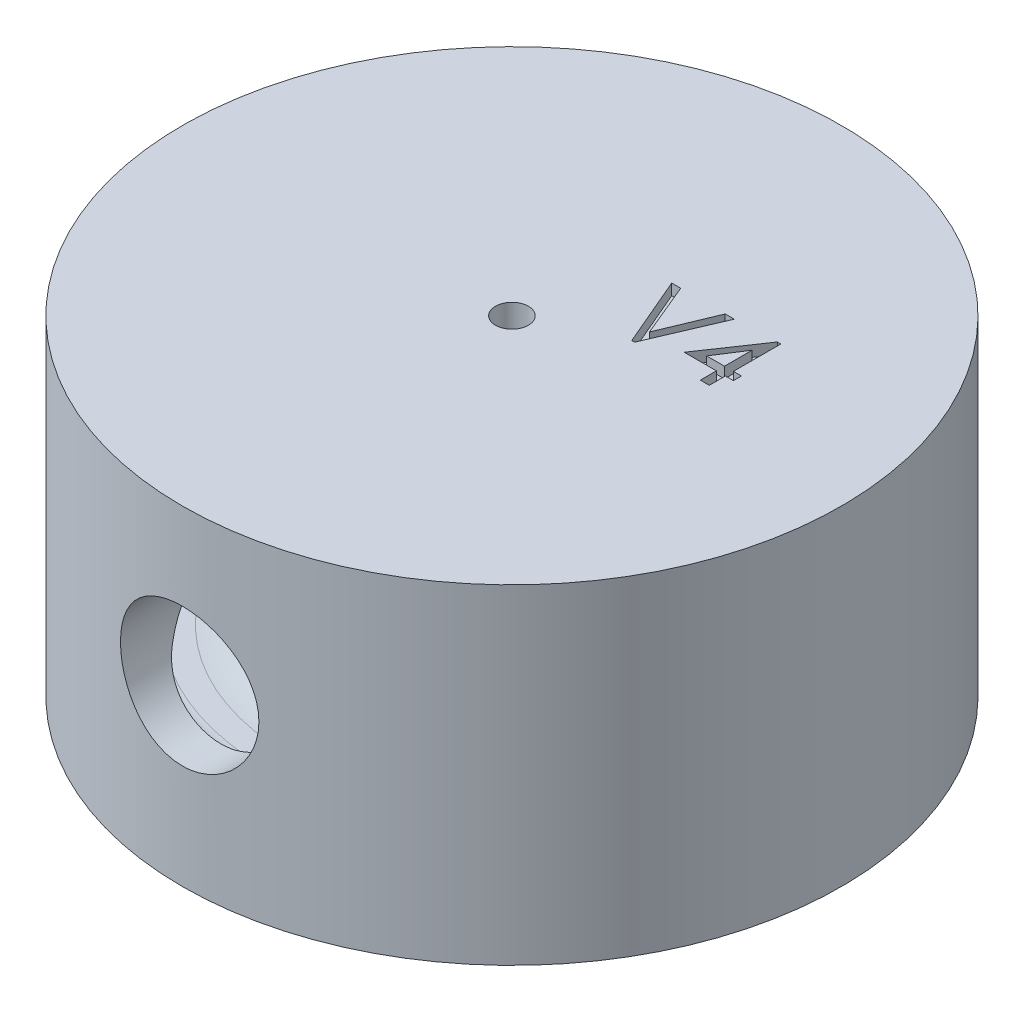
SolidWorks part; units mm, degrees
ref_plane "Front Plane" through (0, 0, 0) normal (0, 0, 1) x (1, 0, 0)
ref_plane "Top Plane" through (0, 0, 0) normal (0, 1, 0) x (1, 0, 0)
ref_plane "Right Plane" through (0, 0, 0) normal (1, 0, 0) x (0, 0, -1)
sketch "Sketch2" plane through (0, 0, 0) normal (0, 0, 1) x (1, 0, 0)
  line L0 (0, 28.7804) -> (0, -27.9337) construction
  line L1 (-36.96, 0.0952) -> (0.75, 0.0952) construction
  line L2 (0, 0.4233) -> (0.75, 0.0952) construction
  line L3 (0.75, 3.3952) -> (0.75, 15.0952)
  line L4 (0.75, 15.0952) -> (15, 15.0952)
  line L5 (15, 15.0952) -> (15, 0.0952)
  line L6 (15, 0.0952) -> (3.25, 0.0952)
  line L7 (1.5, 0.0952) -> (3.1, 0.0952) construction
  line L8 (1.5, 3.3952) -> (1.5, 12.781)
  line L15 (11.307, 2.9209) -> (10.1879, 2.9209)
  line L16 (5.2125, 9.1417) -> (5.414, 10.0359)
  line L17 (5.236, 9.2458) -> (5.0264, 8.3156)
  line L23 (3.25, 0.0952) -> (50.7531, 0.0952) construction
  line L27 (5.236, 9.2458) -> (5.414, 10.0359)
  line L28 (3.25, 11.9898) -> (3.25, 0.9452)
  line L30 (5.414, 10.0359) -> (3.25, 11.9898) construction
  line L32 (3.25, 13.9104) -> (4.2696, 13.9104)
  line L33 (8.5021, 12.9705) -> (8.5893, 12.9298)
  line L36 (10.9047, 10.8775) -> (12.8473, 6.906)
  line L37 (13.2542, 5.1484) -> (13.2542, 4.9209)
  line L38 (3.25, 0.9452) -> (3.1, 0.0952) construction
  line L39 (11.2542, 2.9209) -> (11.307, 2.9209)
  line L41 (1.2, 3.0952) -> (1.05, 3.0952)
  line L42 (3.1, 0.0952) -> (3.25, 0.0952)
  arc A2 (10.1879, 2.9209) -> (5.2125, 9.1417) centre (10.1879, 8.0209) cw
  arc A7 (3.25, 11.9898) -> (5.414, 10.0359) centre (4.332, 11.0129) cw
  arc A9 (1.5, 12.781) -> (3.25, 13.9104) centre (3.25, 11.9898) cw
  arc A10 (8.5021, 12.9705) -> (4.2696, 13.9104) centre (4.2696, 3.9104) ccw
  arc A11 (8.8859, 12.797) -> (8.5893, 12.9298) centre (12.8219, 21.9898) cw
  arc A12 (10.9047, 10.8775) -> (8.8859, 12.797) centre (7.3115, 9.1199) ccw
  arc A13 (12.8473, 6.906) -> (13.2542, 5.1484) centre (9.2542, 5.1484) cw
  arc A14 (11.2542, 2.9209) -> (13.2542, 4.9209) centre (11.2542, 4.9209) ccw
  arc A15 (0.75, 3.3952) -> (1.05, 3.0952) centre (1.05, 3.3952) ccw
  arc A16 (1.5, 3.3952) -> (1.2, 3.0952) centre (1.2, 3.3952) cw
  spline S0 degree 2 poles (3.25, 0.9452) (3.25, 0.9451) (3.25, 0.945) knots 0 0 0 0.000601 0.000601 0.000601
  spline S1 degree 2 poles (3.25, 0.9452) (3.2492, 0.5072) (3.1, 0.0952) knots 0 0 0 1 1 1
  point P42 (5.2348, 9.2405)
  dimension "D7" = 1.1848
  dimension "D8" = 1.6
  dimension "D9" = 5.1
  dimension "D10" = 0.85
  dimension "D11" = 2
  dimension "D14" = 15
  dimension "D6" = 0.3
  dimension "D2" = 15
  dimension "D3" = 15
  dimension "D4" = 1.75
  dimension "D5" = 0.75
revolve "Revolve1" add sketch "Sketch2" angle 360 about L0
sketch3d "3DSketch1"
  circle A0 centre (-0.0074, 5.9778, 15) radius 2.25
  point P2 (-0.0074, 5.9778, 17.25)
sketch "Sketch3" plane through (0, 0, 0) normal (0, 0, 1) x (1, 0, 0)
  circle A0 centre (0, 8) radius 3.15
  dimension "D1" = 6.3
  dimension "D2" = 8
extrude "Cut-Extrude2" cut sketch "Sketch3" along normal through all from offset 8
sketch "Sketch4" plane through (0, 15.0952, 0) normal (0, 1, 0) x (1, 0, 0)
  text T0 "<b>V4</b>"
extrude "Cut-Extrude3" cut sketch "Sketch4" against normal blind 0.5
